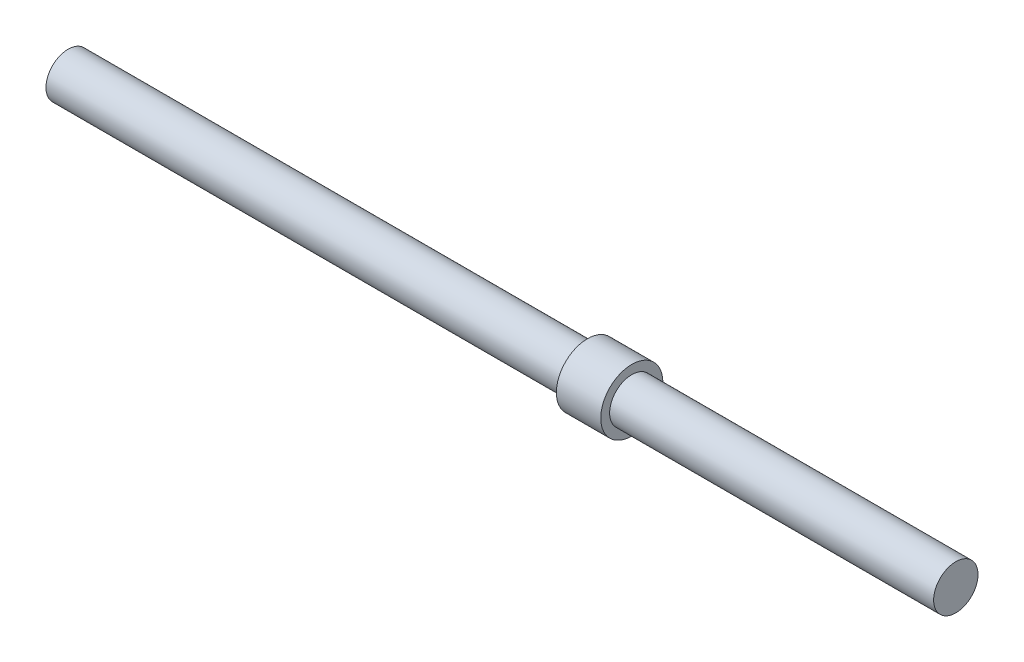
SolidWorks part; units mm, degrees
ref_plane "Front Plane" through (0, 0, 0) normal (0, 0, 1) x (1, 0, 0)
ref_plane "Top Plane" through (0, 0, 0) normal (0, 1, 0) x (1, 0, 0)
ref_plane "Right Plane" through (0, 0, 0) normal (1, 0, 0) x (0, 0, -1)
sketch "Sketch1" plane through (0, 0, 0) normal (1, 0, 0) x (0, 0, -1)
  circle A0 centre (0, 0) radius 5
  dimension "D1" = 10
extrude "Boss-Extrude1" add sketch "Sketch1" along normal mid plane 200
sketch "Sketch3" plane through (0, 0, 0) normal (1, 0, 0) x (0, 0, -1)
  circle A0 centre (0, 0) radius 7
  dimension "D1" = 14
extrude "Boss-Extrude3" add sketch "Sketch3" along normal blind 10 from offset 17
